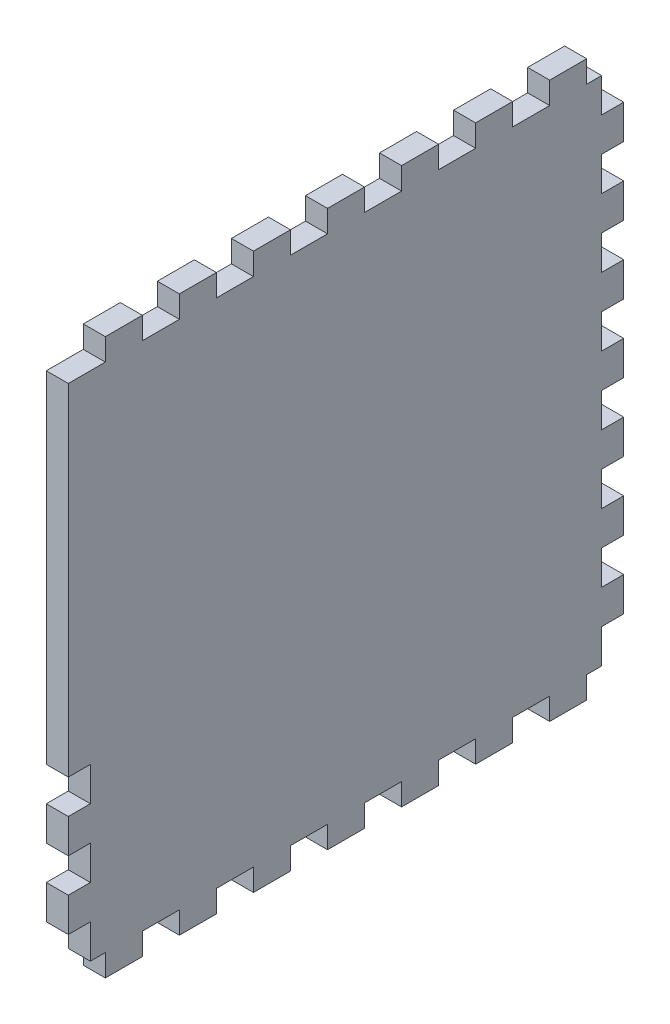
SolidWorks part; units mm, degrees
material "Acrylic (Medium-high impact)"
ref_plane "Front Plane" through (0, 0, 0) normal (0, 0, 1) x (1, 0, 0)
ref_plane "Top Plane" through (0, 0, 0) normal (0, 1, 0) x (1, 0, 0)
ref_plane "Right Plane" through (0, 0, 0) normal (1, 0, 0) x (0, 0, -1)
sketch "Sketch2" plane through (0, 0, 0) normal (1, 0, 0) x (0, 0, -1)
  line L1 (-40, -40) -> (40, -40)
  line L2 (-40, -40) -> (-40, 40)
  line L3 (-40, 40) -> (40, 40)
  line L4 (40, -40) -> (40, 40)
  line L5 (-40, -40) -> (40, 40) construction
  line L6 (-40, 40) -> (40, -40) construction
  point P0 (0, 0)
  dimension "D1" = 80
  dimension "D2" = 80
extrude "Boss-Extrude1" add sketch "Sketch2" along normal blind 3.175
sketch "Sketch3" plane through (3.175, 0, 0) normal (1, 0, 0) x (0, 0, -1)
  line L0 (0, 0) -> (50000, 0) construction
  line L1 (40, -40) -> (40, 40) construction
  line L2 (0, 0) -> (0, 50000) construction
  line L3 (40, 40) -> (-40, 40) construction
  line L6 (-36.825, 36.825) -> (-34.6667, 36.825)
  line L7 (-34.6667, 36.825) -> (-34.6667, 40)
  line L8 (-34.6667, 40) -> (-29.3333, 40)
  line L9 (-24, 40) -> (-18.6667, 40)
  line L10 (-24, 36.825) -> (-24, 40)
  line L11 (-29.3333, 36.825) -> (-24, 36.825)
  line L12 (-29.3333, 40) -> (-29.3333, 36.825)
  line L13 (-13.3333, 40) -> (-8, 40)
  line L14 (-13.3333, 36.825) -> (-13.3333, 40)
  line L15 (-18.6667, 36.825) -> (-13.3333, 36.825)
  line L16 (-18.6667, 40) -> (-18.6667, 36.825)
  line L17 (-2.6667, 40) -> (2.6667, 40)
  line L18 (-2.6667, 36.825) -> (-2.6667, 40)
  line L19 (-8, 36.825) -> (-2.6667, 36.825)
  line L20 (-8, 40) -> (-8, 36.825)
  line L21 (8, 40) -> (13.3333, 40)
  line L22 (8, 36.825) -> (8, 40)
  line L23 (2.6667, 36.825) -> (8, 36.825)
  line L24 (2.6667, 40) -> (2.6667, 36.825)
  line L25 (18.6667, 40) -> (24, 40)
  line L26 (18.6667, 36.825) -> (18.6667, 40)
  line L27 (13.3333, 36.825) -> (18.6667, 36.825)
  line L28 (13.3333, 40) -> (13.3333, 36.825)
  line L29 (29.3333, 40) -> (34.6667, 40)
  line L30 (29.3333, 36.825) -> (29.3333, 40)
  line L31 (24, 36.825) -> (29.3333, 36.825)
  line L32 (24, 40) -> (24, 36.825)
  line L33 (34.6667, -40) -> (34.6667, -36.825)
  line L34 (-40, -40) -> (40, -40) construction
  line L35 (34.6667, 36.825) -> (36.825, 36.825)
  line L36 (34.6667, 40) -> (34.6667, 36.825)
  line L37 (34.6667, -36.825) -> (36.825, -36.825)
  line L38 (-40, 40) -> (-40, -40) construction
  line L39 (24, -40) -> (24, -36.825)
  line L40 (24, -36.825) -> (29.3333, -36.825)
  line L41 (29.3333, -36.825) -> (29.3333, -40)
  line L42 (29.3333, -40) -> (34.6667, -40)
  line L43 (13.3333, -40) -> (13.3333, -36.825)
  line L44 (13.3333, -36.825) -> (18.6667, -36.825)
  line L45 (18.6667, -36.825) -> (18.6667, -40)
  line L46 (18.6667, -40) -> (24, -40)
  line L47 (2.6667, -40) -> (2.6667, -36.825)
  line L48 (2.6667, -36.825) -> (8, -36.825)
  line L49 (8, -36.825) -> (8, -40)
  line L50 (8, -40) -> (13.3333, -40)
  line L51 (-8, -40) -> (-8, -36.825)
  line L52 (-8, -36.825) -> (-2.6667, -36.825)
  line L53 (-2.6667, -36.825) -> (-2.6667, -40)
  line L54 (-2.6667, -40) -> (2.6667, -40)
  line L55 (-18.6667, -40) -> (-18.6667, -36.825)
  line L56 (-18.6667, -36.825) -> (-13.3333, -36.825)
  line L57 (-13.3333, -36.825) -> (-13.3333, -40)
  line L58 (-13.3333, -40) -> (-8, -40)
  line L59 (-29.3333, -40) -> (-29.3333, -36.825)
  line L60 (-29.3333, -36.825) -> (-24, -36.825)
  line L61 (-24, -36.825) -> (-24, -40)
  line L62 (-24, -40) -> (-18.6667, -40)
  line L63 (-34.6667, -40) -> (-29.3333, -40)
  line L64 (-34.6667, -36.825) -> (-34.6667, -40)
  line L65 (-36.825, -36.825) -> (-34.6667, -36.825)
  line L68 (36.825, 36.825) -> (36.825, 31.915)
  line L69 (36.825, 31.915) -> (40, 31.915)
  line L70 (40, 31.915) -> (40, 27.005)
  line L71 (36.825, 27.005) -> (36.825, 22.095)
  line L72 (36.825, 27.005) -> (40, 27.005)
  line L73 (36.825, 22.095) -> (40, 22.095)
  line L74 (40, 22.095) -> (40, 17.185)
  line L75 (36.825, 17.185) -> (36.825, 12.275)
  line L76 (36.825, 17.185) -> (40, 17.185)
  line L77 (36.825, 12.275) -> (40, 12.275)
  line L78 (40, 12.275) -> (40, 7.365)
  line L79 (36.825, 7.365) -> (36.825, 2.455)
  line L80 (36.825, 7.365) -> (40, 7.365)
  line L81 (36.825, 2.455) -> (40, 2.455)
  line L82 (40, 2.455) -> (40, -2.455)
  line L83 (36.825, -2.455) -> (36.825, -7.365)
  line L84 (36.825, -2.455) -> (40, -2.455)
  line L85 (36.825, -7.365) -> (40, -7.365)
  line L86 (40, -7.365) -> (40, -12.275)
  line L87 (36.825, -12.275) -> (36.825, -17.185)
  line L88 (36.825, -12.275) -> (40, -12.275)
  line L89 (36.825, -17.185) -> (40, -17.185)
  line L90 (40, -17.185) -> (40, -22.095)
  line L91 (36.825, -22.095) -> (36.825, -27.005)
  line L92 (36.825, -22.095) -> (40, -22.095)
  line L93 (36.825, -27.005) -> (40, -27.005)
  line L94 (40, -27.005) -> (40, -31.915)
  line L95 (36.825, -31.915) -> (36.825, -36.825)
  line L96 (36.825, -31.915) -> (40, -31.915)
  line L101 (-36.825, -31.915) -> (-40, -31.915)
  line L117 (40, -36.825) -> (40, -41.735) [skipped]
  line L118 (-36.825, -31.915) -> (-36.825, -36.825)
  line L119 (-40, -27.005) -> (-40, -31.915)
  line L120 (-36.825, -27.005) -> (-40, -27.005)
  line L121 (-36.825, -22.095) -> (-40, -22.095)
  line L122 (-36.825, -22.095) -> (-36.825, -27.005)
  line L123 (-40, -17.185) -> (-40, -22.095)
  line L124 (-36.825, -17.185) -> (-40, -17.185)
  line L125 (-36.825, -12.275) -> (-40, -12.275)
  line L126 (-36.825, -12.275) -> (-36.825, -17.185)
  line L127 (-40, -7.365) -> (-40, -12.275)
  line L128 (-36.825, -7.365) -> (-40, -7.365)
  line L129 (-36.825, -2.455) -> (-40, -2.455)
  line L130 (-36.825, -2.455) -> (-36.825, -7.365)
  line L131 (-40, 2.455) -> (-40, -2.455)
  line L132 (-36.825, 2.455) -> (-40, 2.455)
  line L133 (-36.825, 7.365) -> (-40, 7.365)
  line L134 (-36.825, 7.365) -> (-36.825, 2.455)
  line L135 (-40, 12.275) -> (-40, 7.365)
  line L136 (-36.825, 12.275) -> (-40, 12.275)
  line L137 (-36.825, 17.185) -> (-40, 17.185)
  line L138 (-36.825, 17.185) -> (-36.825, 12.275)
  line L139 (-40, 22.095) -> (-40, 17.185)
  line L140 (-36.825, 22.095) -> (-40, 22.095)
  line L141 (-36.825, 27.005) -> (-40, 27.005)
  line L142 (-36.825, 27.005) -> (-36.825, 22.095)
  line L143 (-40, 31.915) -> (-40, 27.005)
  line L144 (-36.825, 31.915) -> (-40, 31.915)
  line L145 (-36.825, 36.825) -> (-36.825, 31.915)
  line L149 (36.825, -36.825) -> (40, -36.825) [skipped]
  point P5 (40, 0)
  point P10 (0, 40)
  point P81 (40, -36.5466)
  dimension "D1" = 3.175
  dimension "D2" = 3.175
  dimension "D3" = 3.175
  dimension "D6" = 8
extrude "Cut-Extrude1" cut sketch "Sketch3" against normal through all flip side to cut
sketch "Sketch5" plane through (0, 0, 0) normal (-1, 0, 0) x (0, 0, 1)
  line L1 (36.825, 36.825) -> (40, 36.825)
  line L2 (36.825, 36.825) -> (36.825, -7.365)
  line L3 (36.825, -7.365) -> (40, -7.365)
  line L4 (40, 36.825) -> (40, -7.365)
extrude "Boss-Extrude3" add sketch "Sketch5" against normal up to surface (3.175 mm away) up to face at (3.175, 0, 0)
